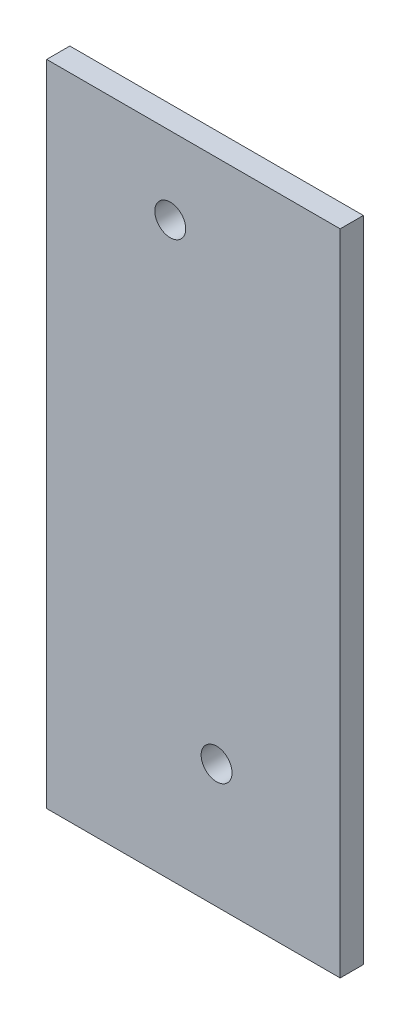
SolidWorks part; units mm, degrees
ref_plane "Plan de face" through (0, 0, 0) normal (0, 0, 1) x (1, 0, 0)
ref_plane "Plan de dessus" through (0, 0, 0) normal (0, 1, 0) x (1, 0, 0)
ref_plane "Plan de droite" through (0, 0, 0) normal (1, 0, 0) x (0, 0, -1)
sketch "Esquisse1" plane through (0, 0, 0) normal (0, 0, 1) x (1, 0, 0)
  line L0 (0, 0) -> (95, 0) construction
  line L1 (0, 0) -> (57, 0) construction
  line L2 (57, 0) -> (57, 165) construction
  line L3 (57, 165) -> (95, 165)
  line L4 (95, 165) -> (95, -155)
  line L5 (95, -155) -> (57, -155)
  line L7 (57, 165) -> (57, -155)
  dimension "D1" = 165
  dimension "D2" = 95
  dimension "D3" = 38
  dimension "D4" = 320
  dimension "D5" = 320
extrude "Boss.-Extru.1" add sketch "Esquisse1" along normal blind 3
sketch "Esquisse2" plane through (0, 0, 3) normal (0, 0, 1) x (1, 0, 0)
  line L2 (95, 165) -> (73, 165) construction
  line L3 (95, 165) -> (57, 165) construction
  line L4 (73, 165) -> (73, 155) construction
  line L5 (73, 155) -> (73, 97) construction
  line L6 (73, 97) -> (79, 97) construction
  circle A1 centre (73, 155) radius 2
  circle A2 centre (79, 97) radius 2
  dimension "D5" = 58
  dimension "D3" = 10
  dimension "D4" = 22
  dimension "D6" = 6
extrude "Enlèv. mat.-Extru.1" cut sketch "Esquisse2" against normal up to next
sketch "Esquisse3" plane through (0, 0, 3) normal (0, 0, 1) x (1, 0, 0)
  line L0 (57, -155) -> (57, 81)
  line L1 (57, 165) -> (57, -155) construction
  line L2 (57, 81) -> (95, 81)
  line L3 (95, -155) -> (95, 165) construction
  line L4 (95, 81) -> (95, -155)
  line L5 (95, -155) -> (57, -155)
extrude "Enlèv. mat.-Extru.2" cut sketch "Esquisse3" against normal up to next
